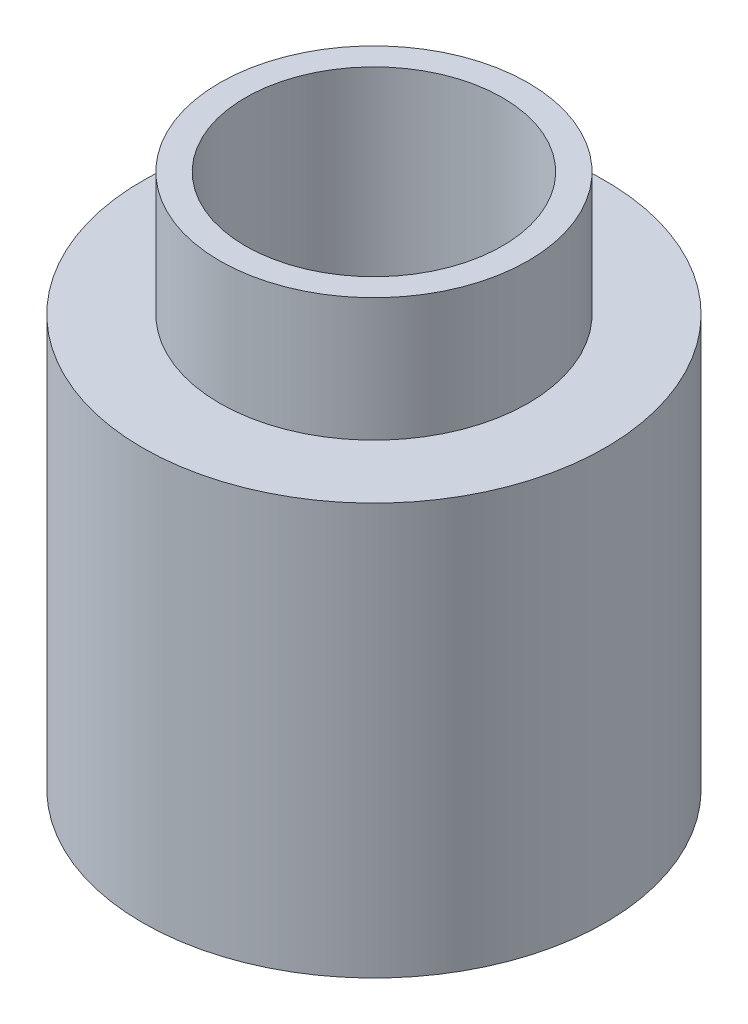
SolidWorks part; units mm, degrees
ref_plane "前视基准面" through (0, 0, 0) normal (0, 0, 1) x (1, 0, 0)
ref_plane "上视基准面" through (0, 0, 0) normal (0, 1, 0) x (1, 0, 0)
ref_plane "右视基准面" through (0, 0, 0) normal (1, 0, 0) x (0, 0, -1)
other "Configuration Table"
sketch "草图1" plane through (0, 0, 0) normal (0, 1, 0) x (1, 0, 0)
  circle A0 centre (0, 0) radius 2.25
  circle A1 centre (0, 0) radius 1.25
  dimension "D1" = 4.5
  dimension "D2" = 2.5
extrude "凸台-拉伸1" add sketch "草图1" along normal blind 4
sketch "草图2" plane through (0, 4, 0) normal (0, 1, 0) x (1, 0, 0)
  circle A0 centre (0, 0) radius 1.25
  circle A1 centre (0, 0) radius 1.5
  dimension "D1" = 3
extrude "凸台-拉伸2" add sketch "草图2" along normal blind 1.2
